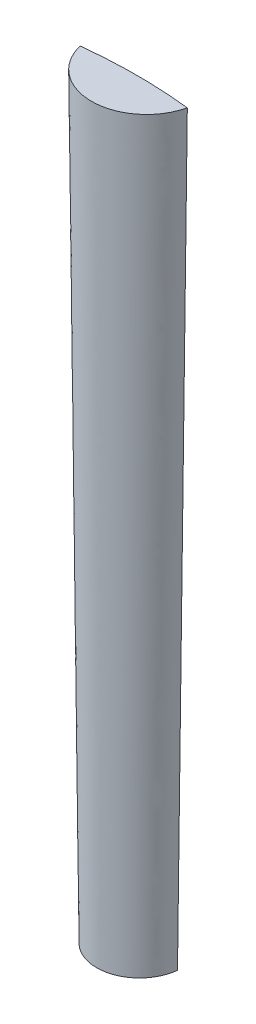
SolidWorks part; units mm, degrees
material "Maple"
ref_plane "Front Plane" through (0, 0, 0) normal (0, 0, 1) x (1, 0, 0)
ref_plane "Top Plane" through (0, 0, 0) normal (0, 1, 0) x (1, 0, 0)
ref_plane "Right Plane" through (0, 0, 0) normal (1, 0, 0) x (0, 0, -1)
sketch "Model" plane through (0, 0, 0) normal (0, 0, 1) x (1, 0, 0)
  line L0 (47.9999, 0) -> (57.149, 660.4)
  line L1 (40.86, 0) -> (46.3494, 660.4)
  line L2 (33.72, 0) -> (35.5498, 660.4)
  line L3 (26.5801, 0) -> (24.7503, 660.4)
  line L4 (19.4401, 0) -> (13.9507, 660.4)
  line L5 (12.3002, 0) -> (3.1511, 660.4)
  line L6 (51.151, 0) -> (60.3001, 660.4)
  line L7 (9.1491, 0) -> (0, 660.4)
  line L8 (51.659, 0) -> (43.9219, 0)
  line L9 (52.1725, 37.0654) -> (44.3327, 37.0654)
  line L10 (52.6572, 72.0505) -> (44.7205, 72.0505)
  line L11 (53.1147, 105.072) -> (45.0865, 105.072)
  line L12 (53.5465, 136.2402) -> (45.4319, 136.2402)
  line L13 (53.954, 165.659) -> (45.7579, 165.659)
  line L14 (54.3387, 193.4267) -> (46.0657, 193.4267)
  line L15 (54.7018, 219.6359) -> (46.3562, 219.6359)
  line L16 (55.0445, 244.3741) -> (46.6304, 244.3741)
  line L17 (55.368, 267.7238) -> (46.8891, 267.7238)
  line L18 (55.6734, 289.763) -> (47.1334, 289.763)
  line L19 (55.9616, 310.5653) -> (47.364, 310.5653)
  line L20 (56.2336, 330.2) -> (47.5816, 330.2)
  line L21 (56.4903, 348.7327) -> (47.787, 348.7327)
  line L22 (56.7327, 366.2252) -> (47.9808, 366.2252)
  line L23 (56.9614, 382.736) -> (48.1638, 382.736)
  line L24 (57.1773, 398.3201) -> (48.3365, 398.3201)
  line L25 (57.3811, 413.0295) -> (48.4996, 413.0295)
  line L26 (57.5734, 426.9133) -> (48.6534, 426.9133)
  line L27 (57.755, 440.0179) -> (48.7987, 440.0179)
  line L28 (57.9263, 452.387) -> (48.9358, 452.387)
  line L29 (58.0881, 464.0619) -> (49.0652, 464.0619)
  line L30 (58.2407, 475.0815) -> (49.1873, 475.0815)
  line L31 (58.3848, 485.4826) -> (49.3026, 485.4826)
  line L32 (58.5208, 495.3) -> (49.4114, 495.3)
  line L33 (44.9379, 0) -> (36.782, 0)
  line L34 (45.3487, 37.0654) -> (36.9874, 37.0654)
  line L35 (45.7365, 72.0505) -> (37.1813, 72.0505)
  line L36 (46.1025, 105.072) -> (37.3643, 105.072)
  line L37 (46.4479, 136.2402) -> (37.537, 136.2402)
  line L38 (46.7739, 165.659) -> (37.7, 165.659)
  line L39 (47.0817, 193.4267) -> (37.8539, 193.4267)
  line L40 (47.3722, 219.6359) -> (37.9991, 219.6359)
  line L41 (47.6464, 244.3741) -> (38.1362, 244.3741)
  line L42 (47.9051, 267.7238) -> (38.2656, 267.7238)
  line L43 (48.1494, 289.763) -> (38.3877, 289.763)
  line L44 (48.38, 310.5653) -> (38.503, 310.5653)
  line L45 (48.5976, 330.2) -> (38.6118, 330.2)
  line L46 (48.803, 348.7327) -> (38.7145, 348.7327)
  line L47 (48.9968, 366.2252) -> (38.8114, 366.2252)
  line L48 (49.1798, 382.736) -> (38.9029, 382.736)
  line L49 (49.3525, 398.3201) -> (38.9893, 398.3201)
  line L50 (49.5156, 413.0295) -> (39.0708, 413.0295)
  line L51 (49.6694, 426.9133) -> (39.1478, 426.9133)
  line L52 (49.8147, 440.0179) -> (39.2204, 440.0179)
  line L53 (49.9518, 452.387) -> (39.2889, 452.387)
  line L54 (50.0812, 464.0619) -> (39.3536, 464.0619)
  line L55 (50.2033, 475.0815) -> (39.4147, 475.0815)
  line L56 (50.3186, 485.4826) -> (39.4723, 485.4826)
  line L57 (50.4274, 495.3) -> (39.5267, 495.3)
  line L58 (37.798, 0) -> (29.6421, 0)
  line L59 (38.0034, 37.0654) -> (29.6421, 37.0654)
  line L60 (38.1973, 72.0505) -> (29.6421, 72.0505)
  line L61 (38.3803, 105.072) -> (29.6421, 105.072)
  line L62 (38.553, 136.2402) -> (29.6421, 136.2402)
  line L63 (38.716, 165.659) -> (29.6421, 165.659)
  line L64 (38.8699, 193.4267) -> (29.6421, 193.4267)
  line L65 (39.0151, 219.6359) -> (29.6421, 219.6359)
  line L66 (39.1522, 244.3741) -> (29.6421, 244.3741)
  line L67 (39.2816, 267.7238) -> (29.6421, 267.7238)
  line L68 (39.4037, 289.763) -> (29.6421, 289.763)
  line L69 (39.519, 310.5653) -> (29.6421, 310.5653)
  line L70 (39.6278, 330.2) -> (29.6421, 330.2)
  line L71 (39.7305, 348.7327) -> (29.6421, 348.7327)
  line L72 (39.8274, 366.2252) -> (29.6421, 366.2252)
  line L73 (39.9189, 382.736) -> (29.6421, 382.736)
  line L74 (40.0053, 398.3201) -> (29.6421, 398.3201)
  line L75 (40.0868, 413.0295) -> (29.6421, 413.0295)
  line L76 (40.1638, 426.9133) -> (29.6421, 426.9133)
  line L77 (40.2364, 440.0179) -> (29.6421, 440.0179)
  line L78 (40.3049, 452.387) -> (29.6421, 452.387)
  line L79 (40.3696, 464.0619) -> (29.6421, 464.0619)
  line L80 (40.4307, 475.0815) -> (29.6421, 475.0815)
  line L81 (40.4883, 485.4826) -> (29.6421, 485.4826)
  line L82 (40.5427, 495.3) -> (29.6421, 495.3)
  line L83 (30.6581, 0) -> (22.5021, 0)
  line L84 (30.6581, 37.0654) -> (22.2967, 37.0654)
  line L85 (30.6581, 72.0505) -> (22.1028, 72.0505)
  line L86 (30.6581, 105.072) -> (21.9199, 105.072)
  line L87 (30.6581, 136.2402) -> (21.7471, 136.2402)
  line L88 (30.6581, 165.659) -> (21.5841, 165.659)
  line L89 (30.6581, 193.4267) -> (21.4302, 193.4267)
  line L90 (30.6581, 219.6359) -> (21.285, 219.6359)
  line L91 (30.6581, 244.3741) -> (21.1479, 244.3741)
  line L92 (30.6581, 267.7238) -> (21.0185, 267.7238)
  line L93 (30.6581, 289.763) -> (20.8964, 289.763)
  line L94 (30.6581, 310.5653) -> (20.7811, 310.5653)
  line L95 (30.6581, 330.2) -> (20.6723, 330.2)
  line L96 (30.6581, 348.7327) -> (20.5696, 348.7327)
  line L97 (30.6581, 366.2252) -> (20.4727, 366.2252)
  line L98 (30.6581, 382.736) -> (20.3812, 382.736)
  line L99 (30.6581, 398.3201) -> (20.2948, 398.3201)
  line L100 (30.6581, 413.0295) -> (20.2133, 413.0295)
  line L101 (30.6581, 426.9133) -> (20.1364, 426.9133)
  line L102 (30.6581, 440.0179) -> (20.0637, 440.0179)
  line L103 (30.6581, 452.387) -> (19.9952, 452.387)
  line L104 (30.6581, 464.0619) -> (19.9305, 464.0619)
  line L105 (30.6581, 475.0815) -> (19.8694, 475.0815)
  line L106 (30.6581, 485.4826) -> (19.8118, 485.4826)
  line L107 (30.6581, 495.3) -> (19.7574, 495.3)
  line L108 (23.5181, 0) -> (15.3622, 0)
  line L109 (23.3127, 37.0654) -> (14.9514, 37.0654)
  line L110 (23.1188, 72.0505) -> (14.5636, 72.0505)
  line L111 (22.9359, 105.072) -> (14.1977, 105.072)
  line L112 (22.7631, 136.2402) -> (13.8522, 136.2402)
  line L113 (22.6001, 165.659) -> (13.5262, 165.659)
  line L114 (22.4462, 193.4267) -> (13.2184, 193.4267)
  line L115 (22.301, 219.6359) -> (12.9279, 219.6359)
  line L116 (22.1639, 244.3741) -> (12.6538, 244.3741)
  line L117 (22.0345, 267.7238) -> (12.395, 267.7238)
  line L118 (21.9124, 289.763) -> (12.1507, 289.763)
  line L119 (21.7971, 310.5653) -> (11.9202, 310.5653)
  line L120 (21.6883, 330.2) -> (11.7025, 330.2)
  line L121 (21.5856, 348.7327) -> (11.4971, 348.7327)
  line L122 (21.4887, 366.2252) -> (11.3033, 366.2252)
  line L123 (21.3972, 382.736) -> (11.1203, 382.736)
  line L124 (21.3108, 398.3201) -> (10.9476, 398.3201)
  line L125 (21.2293, 413.0295) -> (10.7845, 413.0295)
  line L126 (21.1524, 426.9133) -> (10.6307, 426.9133)
  line L127 (21.0797, 440.0179) -> (10.4854, 440.0179)
  line L128 (21.0112, 452.387) -> (10.3483, 452.387)
  line L129 (20.9465, 464.0619) -> (10.2189, 464.0619)
  line L130 (20.8854, 475.0815) -> (10.0968, 475.0815)
  line L131 (20.8278, 485.4826) -> (9.9815, 485.4826)
  line L132 (20.7734, 495.3) -> (9.8727, 495.3)
  line L133 (16.3782, 0) -> (8.6411, 0)
  line L134 (15.9674, 37.0654) -> (8.1276, 37.0654)
  line L135 (15.5796, 72.0505) -> (7.6429, 72.0505)
  line L136 (15.2137, 105.072) -> (7.1854, 105.072)
  line L137 (14.8682, 136.2402) -> (6.7536, 136.2402)
  line L138 (14.5422, 165.659) -> (6.3461, 165.659)
  line L139 (14.2344, 193.4267) -> (5.9614, 193.4267)
  line L140 (13.9439, 219.6359) -> (5.5983, 219.6359)
  line L141 (13.6698, 244.3741) -> (5.2556, 244.3741)
  line L142 (13.411, 267.7238) -> (4.9321, 267.7238)
  line L143 (13.1667, 289.763) -> (4.6267, 289.763)
  line L144 (12.9362, 310.5653) -> (4.3386, 310.5653)
  line L145 (12.7185, 330.2) -> (4.0665, 330.2)
  line L146 (12.5131, 348.7327) -> (3.8098, 348.7327)
  line L147 (12.3193, 366.2252) -> (3.5675, 366.2252)
  line L148 (12.1363, 382.736) -> (3.3387, 382.736)
  line L149 (11.9636, 398.3201) -> (3.1228, 398.3201)
  line L150 (11.8005, 413.0295) -> (2.919, 413.0295)
  line L151 (11.6467, 426.9133) -> (2.7267, 426.9133)
  line L152 (11.5014, 440.0179) -> (2.5451, 440.0179)
  line L153 (11.3643, 452.387) -> (2.3738, 452.387)
  line L154 (11.2349, 464.0619) -> (2.212, 464.0619)
  line L155 (11.1128, 475.0815) -> (2.0594, 475.0815)
  line L156 (10.9975, 485.4826) -> (1.9153, 485.4826)
  line L157 (10.8887, 495.3) -> (1.7793, 495.3)
ref_plane "Plane1" through (0, 37.07, 0) normal (0, 1, 0) x (1, 0, 0)
ref_plane "Plane2" through (0, 413.03, 0) normal (0, 1, 0) x (1, 0, 0)
sketch "Sketch2" plane through (0, 37.07, 0) normal (0, 1, 0) x (1, 0, 0)
  line L0 (22.5021, 0) -> (37.798, 0) construction
  line L4 (30.6581, 0) -> (22.5021, 0) construction
  line L5 (30.6581, 0) -> (22.2967, 0) construction
  line L6 (37.798, 0) -> (29.6421, 0) construction
  line L7 (30.1501, 0) -> (30.1501, -241.3) construction
  line L8 (30.1501, 0) -> (30.1501, -20) construction
  line L9 (30.1501, 0) -> (30.1501, 60) construction
  line L10 (8.7751, 0) -> (51.5251, 0) construction
  arc A0 (51.4416, -0.9412) -> (8.8585, -0.9412) centre (30.1501, -241.3) ccw
  arc A1 (8.7751, 0) -> (8.8585, -0.9412) centre (30.1501, 1.4219) ccw construction
  arc A3 (8.8585, -0.9412) -> (51.4416, -0.9412) centre (30.1501, 1.4219) ccw
  point P17 (30.1501, 0)
  dimension "D1" = 241.3
  dimension "D2" = 20
  dimension "D3" = 60
  dimension "D4" = 42.75
sketch "Sketch4" plane through (0, 413.03, 0) normal (0, 1, 0) x (1, 0, 0)
  line L0 (37.798, 0) -> (22.5021, 0) construction
  line L1 (37.798, 0) -> (29.6421, 0) construction
  line L2 (44.9379, 0) -> (36.782, 0) construction
  line L3 (30.6581, 0) -> (22.5021, 0) construction
  line L4 (30.6581, 0) -> (22.2967, 0) construction
  line L5 (30.1501, 0) -> (30.1501, -241.3) construction
  line L6 (30.1501, 0) -> (30.1501, -22.6) construction
  line L7 (57.2001, 0) -> (3.1001, 0) construction
  circle A0 centre (30.1501, -241.3) radius 241.3 construction
  arc A1 (57.2001, 0) -> (56.8889, -1.4861) centre (30.1501, 4.8875) cw construction
  arc A2 (3.4112, -1.4861) -> (56.8889, -1.4861) centre (30.1501, -241.3) cw
  arc A3 (3.4112, -1.4861) -> (3.1001, 0) centre (30.1501, 4.8875) cw construction
  arc A4 (56.8889, -1.4861) -> (3.4112, -1.4861) centre (30.1501, 4.8875) cw
  point P18 (30.1501, 0)
  dimension "D1" = 241.3
  dimension "D2" = 22.6
  dimension "D3" = 54.1
loft "Loft1" add profiles "Sketch4", "Sketch2"
sketch "Sketch5" plane through (0, 0, 0) normal (0, 0, 1) x (1, 0, 0)
  line L0 (51.151, 0) -> (51.151, -3.25) construction
  line L1 (51.151, -3.25) -> (9.1491, -3.25) construction
  line L2 (9.1491, -3.25) -> (9.1491, 0) construction
  line L3 (51.151, 0) -> (9.1491, 0) construction
  line L10 (47.9999, 0) -> (47.9999, -42) construction
  line L11 (40.86, 0) -> (40.86, -66) construction
  line L12 (33.72, 0) -> (33.72, -90) construction
  line L13 (26.5801, 0) -> (26.5801, -114) construction
  line L14 (19.4401, 0) -> (19.4401, -138) construction
  line L15 (12.3002, 0) -> (12.3002, -162) construction
  dimension "D1" = 3.25
  dimension "D2" = 42
  dimension "D3" = 66
  dimension "D4" = 90
  dimension "D5" = 114
  dimension "D6" = 138
  dimension "D7" = 162
sketch "Sketch7" plane through (0, 0, 0) normal (0, 0, 1) x (1, 0, 0)
  line L0 (47.9999, -42) -> (50.7999, -42) construction
  line L1 (40.86, -66) -> (43.66, -66) construction
  line L2 (33.72, -90) -> (36.52, -90) construction
  line L3 (26.5801, -114) -> (29.3801, -114) construction
  line L4 (19.4401, -138) -> (22.2401, -138) construction
  line L5 (12.3002, -162) -> (15.1002, -162) construction
  line L6 (50.7999, -42) -> (15.1002, -162) construction
  line L7 (61.8225, -45.2792) -> (26.1228, -165.2792)
  line L8 (61.8225, -45.2792) -> (79.2285, 13.2291)
  line L9 (26.1228, -165.2792) -> (5.0038, -236.2679)
  line L10 (9.1491, -3.25) -> (9.1491, -15.8462)
  line L20 (51.151, 0) -> (51.151, -3.25)
  line L21 (51.151, -3.25) -> (52.9795, -13.3945)
  line L22 (52.9795, -13.3945) -> (59.8676, -22.9535)
  line L24 (59.8676, -22.9535) -> (62.3906, -26.4548)
  line L25 (62.3906, -26.4548) -> (64.4679, -36.3869)
  circle A0 centre (50.7999, -42) radius 5
  circle A6 centre (43.66, -66) radius 5
  circle A7 centre (36.52, -90) radius 5
  circle A8 centre (29.3801, -114) radius 5
  circle A9 centre (22.2401, -138) radius 5
  circle A10 centre (15.1002, -162) radius 5
  circle A11 centre (50.7999, -42) radius 7 construction
  circle A12 centre (43.66, -66) radius 7 construction
  circle A13 centre (36.52, -90) radius 7 construction
  circle A14 centre (29.3801, -114) radius 7 construction
  circle A15 centre (22.2401, -138) radius 7 construction
  circle A16 centre (15.1002, -162) radius 7 construction
  ellipse E0 centre (1.251, -166.4127) end of major axis (17.5357, -184.8658) minor radius 20.6878
  spline S3 degree 3 poles (9.1491, -15.8462) (9.1473, -28.5049) (1.4139, -41.2504) (-15.1408, -58.1769) (-12.1006, -78.7152) (-6.0827, -97.5099) (3.173, -117.7749) (-1.2779, -143.1565) (-13.0261, -147.3332) (-15.0337, -147.9597) knots 0 0 0 0 0.241122 0.31589 0.476811 0.625348 0.735304 0.956701 1 1 1 1
  point P32 (-11.464, -78.6541)
  point P36 (-5.1076, -99.0182)
  point P37 (-12.4923, -147.0912)
  point P38 (3.3632, -36.3869)
  dimension "D7" = 10
  dimension "D8" = 10
  dimension "D9" = 10
  dimension "D10" = 10
  dimension "D11" = 10
  dimension "D12" = 10
  dimension "D13" = 11.5
  dimension "D1" = 2.8
  dimension "D2" = 2.8
  dimension "D3" = 2.8
  dimension "D4" = 2.8
  dimension "D5" = 2.8
  dimension "D6" = 2.8
